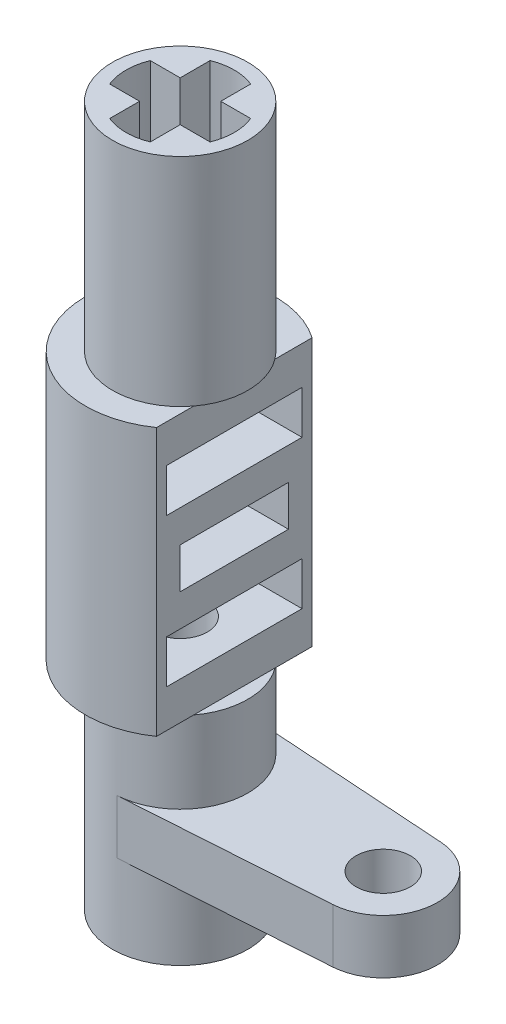
SolidWorks part; units mm, degrees
ref_plane "前视基准面" through (0, 0, 0) normal (0, 0, 1) x (1, 0, 0)
ref_plane "上视基准面" through (0, 0, 0) normal (0, 1, 0) x (1, 0, 0)
ref_plane "右视基准面" through (0, 0, 0) normal (1, 0, 0) x (0, 0, -1)
other "Configuration Table"
sketch "草图1" plane through (0, 0, 0) normal (0, 1, 0) x (1, 0, 0)
  circle A0 centre (0, 0) radius 2.5
  dimension "D1" = 5
extrude "凸台-拉伸1" add sketch "草图1" along normal blind 25.88
sketch "草图2" plane through (0, 0, 0) normal (0, 1, 0) x (1, 0, 0)
  line L0 (-1000, 0) -> (49000, 0) construction
  line L1 (0.1667, 2.4944) -> (7.6333, 1.9956)
  line L2 (0.1667, -2.4944) -> (7.6333, -1.9956)
  circle A0 centre (0, 0) radius 2.5 construction
  arc A1 (0.1667, 2.4944) -> (0.1667, -2.4944) centre (0, 0) ccw
  arc A2 (7.6333, -1.9956) -> (7.6333, 1.9956) centre (7.5, 0) ccw
  circle A3 centre (7.5, 0) radius 1
  dimension "D1" = 4
  dimension "D3" = 2
  dimension "D2" = 7.5
extrude "凸台-拉伸2" add sketch "草图2" along normal blind 2 from offset 3
sketch "草图3" plane through (0, 0, 0) normal (0, 1, 0) x (1, 0, 0)
  line L0 (-1000, 0) -> (49000, 0) construction
  line L1 (0, -1000) -> (0, 49000) construction
  line L4 (-1.854, -0.75) -> (-0.75, -0.75)
  line L6 (1.854, 0.75) -> (0.75, 0.75)
  line L7 (-0.75, 1.854) -> (-0.75, 0.75)
  line L9 (0.75, -1.854) -> (0.75, -0.75)
  line L10 (0.75, -0.75) -> (1.854, -0.75)
  line L11 (-0.75, -0.75) -> (-0.75, -1.854)
  line L12 (0.75, 0.75) -> (0.75, 1.854)
  line L13 (-0.75, 0.75) -> (-1.854, 0.75)
  arc A0 (-1.854, 0.75) -> (-1.854, -0.75) centre (0, 0) ccw
  arc A1 (0.75, 1.854) -> (-0.75, 1.854) centre (0, 0) ccw
  arc A2 (1.854, -0.75) -> (1.854, 0.75) centre (0, 0) ccw
  arc A3 (-0.75, -1.854) -> (0.75, -1.854) centre (0, 0) ccw
  point P10 (0, 1.854)
  point P13 (-1.854, 0)
  dimension "D1" = 4
  dimension "D2" = 1.5
  dimension "D3" = 1.5
  dimension "D4" = 1.104
  dimension "D5" = 2.1213
extrude "切除-拉伸1" cut sketch "草图3" along normal blind 4 contours L10 A2 L6 L12 A1 L7 L13 A0 L4 L11 L9
sketch "草图5" plane through (0, 0, 0) normal (0, 1, 0) x (1, 0, 0)
  line L0 (1.854, 0.75) -> (0.75, 0.75) construction
  line L1 (0.75, 0.75) -> (0.75, 1.854) construction
  line L2 (-0.75, 1.854) -> (-0.75, 0.75) construction
  line L3 (-0.75, 0.75) -> (-1.854, 0.75) construction
  line L4 (-0.75, -0.75) -> (-0.75, -1.854) construction
  line L5 (0.75, -1.854) -> (0.75, -0.75) construction
  line L6 (-1.854, -0.75) -> (-0.75, -0.75) construction
  line L7 (0.75, -0.75) -> (1.854, -0.75) construction
  line L8 (1.854, 0.75) -> (0.75, 0.75)
  line L9 (0.75, 0.75) -> (0.75, 1.854)
  line L10 (-0.75, 1.854) -> (-0.75, 0.75)
  line L11 (-0.75, 0.75) -> (-1.854, 0.75)
  line L12 (-0.75, -0.75) -> (-0.75, -1.854)
  line L13 (0.75, -1.854) -> (0.75, -0.75)
  line L14 (-1.854, -0.75) -> (-0.75, -0.75)
  line L15 (0.75, -0.75) -> (1.854, -0.75)
  arc A0 (0.75, 1.854) -> (-0.75, 1.854) centre (0, 0) ccw construction
  arc A1 (-1.854, 0.75) -> (-1.854, -0.75) centre (0, 0) ccw construction
  arc A2 (-0.75, -1.854) -> (0.75, -1.854) centre (0, 0) ccw construction
  arc A3 (1.854, -0.75) -> (1.854, 0.75) centre (0, 0) ccw construction
  arc A4 (0.75, 1.854) -> (-0.75, 1.854) centre (0, 0) ccw
  arc A5 (-1.854, 0.75) -> (-1.854, -0.75) centre (0, 0) ccw
  arc A6 (-0.75, -1.854) -> (0.75, -1.854) centre (0, 0) ccw
  arc A7 (1.854, -0.75) -> (1.854, 0.75) centre (0, 0) ccw
extrude "切除-拉伸2" cut sketch "草图5" against normal blind 4 from surface at 25.88 starting at face at (0, 25.88, 2.5)
sketch "草图6" plane through (0, 0, 0) normal (0, 1, 0) x (1, 0, 0)
  line L0 (0, 0) -> (0.75, 0) construction
  circle A0 centre (0.75, 0) radius 0.25
  dimension "D2" = 0.5
  dimension "D1" = 0.75
extrude "切除-拉伸3" cut sketch "草图6" against normal blind 0.25 from surface at 21.88 starting at face at (0, 21.88, 0)
sketch "草图7" plane through (0, 0, 0) normal (0, 1, 0) x (1, 0, 0)
  circle A0 centre (0.75, 0) radius 0.25 construction
  circle A1 centre (0.75, 0) radius 0.25
extrude "切除-拉伸4" cut sketch "草图7" along normal blind 0.25 from surface at 4 starting at face at (0, 4, 0)
sketch "草图17" plane through (0, 0, 0) normal (0, 1, 0) x (1, 0, 0)
  circle A0 centre (0, 0) radius 3.5
  dimension "D1" = 7
extrude "凸台-拉伸5" add sketch "草图17" along normal blind 9.88 from offset 8
sketch "草图18" plane through (0, 0, 0) normal (0, 1, 0) x (1, 0, 0)
  circle A0 centre (0, 0) radius 1
  dimension "D1" = 2
extrude "切除-拉伸11" cut sketch "草图18" along normal blind 10
sketch "草图19" plane through (0, 0, 0) normal (0, 1, 0) x (1, 0, 0)
  circle A0 centre (0, 0) radius 1
  dimension "D1" = 2
extrude "切除-拉伸12" cut sketch "草图19" against normal blind 10 from surface at 25.88 starting at face at (0, 25.88, 2.5)
sketch "草图20" plane through (0, 0, 0) normal (0, 0, 1) x (1, 0, 0)
  line L0 (0, -1000) -> (0, 49000) construction
  line L1 (-2, 14.88) -> (2, 14.88)
  line L2 (2, 14.88) -> (2, 16.48)
  line L3 (2, 16.48) -> (-2, 16.48)
  line L4 (-2, 16.48) -> (-2, 14.88)
  line L5 (0.75, 21.88) -> (-0.75, 21.88) construction
  line L6 (-2, 11) -> (2, 11)
  line L7 (2, 11) -> (2, 9.4)
  line L8 (2, 9.4) -> (-2, 9.4)
  line L9 (-2, 9.4) -> (-2, 11)
  line L10 (-1, 4) -> (1, 4) construction
  point P6 (0, 14.88)
  point P13 (0, 11)
  dimension "D1" = 4
  dimension "D2" = 1.6
  dimension "D3" = 7
  dimension "D4" = 1.6
  dimension "D5" = 4
  dimension "D6" = 5.4
extrude "切除-拉伸13" cut sketch "草图20" against normal blind 2.5 and the other way blind 2.5
sketch "草图21" plane through (0, 0, 0) normal (0, 0, 1) x (1, 0, 0)
  line L0 (3.5, 17.88) -> (2, 17.88)
  line L1 (3.5, 17.88) -> (-3.5, 17.88) construction
  line L2 (2, 17.88) -> (2, 8)
  line L3 (-2.5, 8) -> (2.5, 8) construction
  line L4 (2, 8) -> (3.5, 8)
  line L5 (-3.5, 8) -> (3.5, 8) construction
  line L6 (3.5, 8) -> (3.5, 17.88)
  line L7 (-2, 16.48) -> (-2, 14.88) construction
  dimension "D1" = 1.5
  dimension "D2" = 4
extrude "切除-拉伸14" cut sketch "草图21" against normal through all and the other way through all
sketch "草图22" plane through (0, 0, 0) normal (1, 0, 0) x (0, 0, -1)
  line L0 (2.5, 14.88) -> (-2.5, 11) construction
  line L1 (-2.5, 11) -> (-2.5, 9.4) construction
  line L2 (-2.5, 11) -> (2.5, 11) construction
  line L3 (-2.5, 14.88) -> (2.5, 11) construction
  line L5 (-2, 13.69) -> (2, 13.69)
  line L6 (-2, 13.69) -> (-2, 12.19)
  line L7 (-2, 12.19) -> (2, 12.19)
  line L8 (2, 13.69) -> (2, 12.19)
  line L9 (-2, 13.69) -> (2, 12.19) construction
  line L10 (-2, 12.19) -> (2, 13.69) construction
  point P11 (0, 12.94)
  point P16 (0, 0)
  point P17 (0, 0)
  point P18 (0, 0)
  point P19 (0, 0)
  point P21 (0, 0)
  point P22 (0, 0)
  point P24 (0, 0)
  point P25 (0, 0)
  dimension "D1" = 1.5
  dimension "D2" = 4
extrude "切除-拉伸15" cut sketch "草图22" along normal through all
